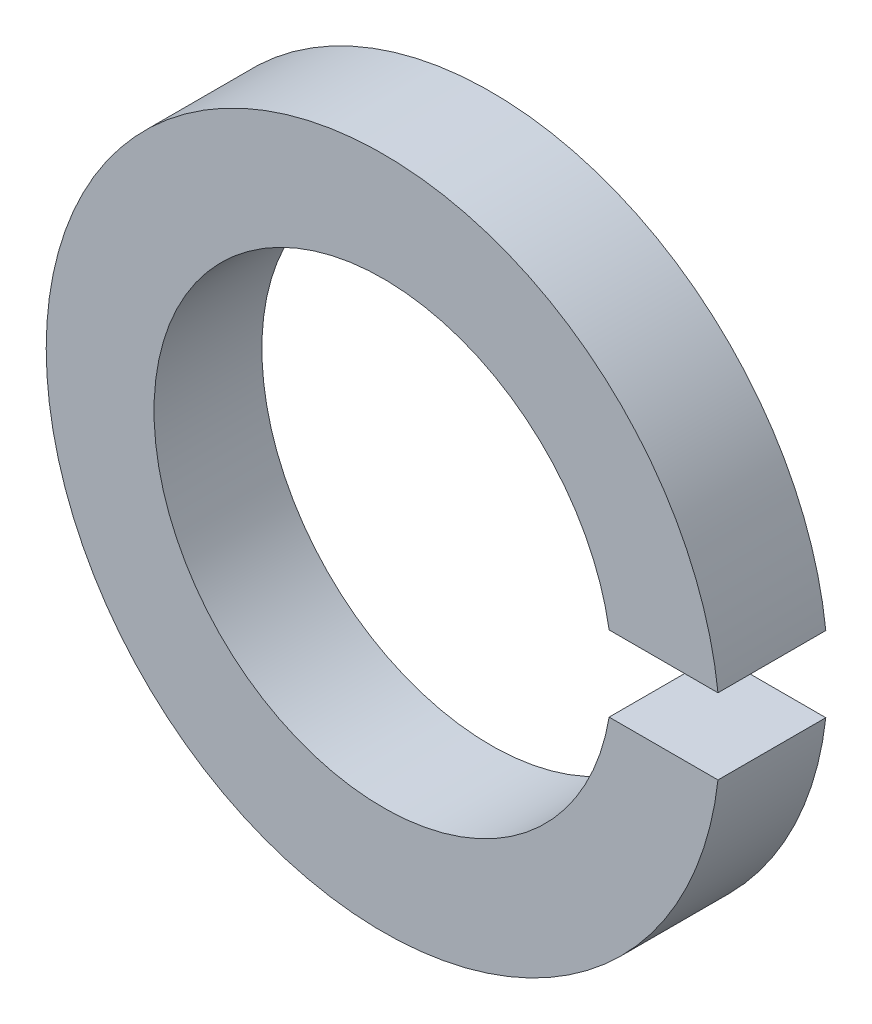
SolidWorks part; units mm, degrees
ref_plane "Спереди" through (0, 0, 0) normal (0, 0, 1) x (1, 0, 0)
ref_plane "Сверху" through (0, 0, 0) normal (0, 1, 0) x (1, 0, 0)
ref_plane "Справа" through (0, 0, 0) normal (1, 0, 0) x (0, 0, -1)
sketch "Эскиз1" plane through (0, 0, 0) normal (0, 0, 1) x (1, 0, 0)
  circle A0 centre (0, 0) radius 3.75
  circle A1 centre (0, 0) radius 2.55
  dimension "D1" = 7.5
  dimension "D2" = 5.1
extrude "Вытянуть1" add sketch "Эскиз1" along normal blind 1.2
sketch "Эскиз2" plane through (0, 0, 1.2) normal (0, 0, 1) x (1, 0, 0)
  line L0 (0, 0) -> (0.123, 0) construction
  line L1 (3.75, 0) -> (-3.75, 0) construction
  line L3 (2.4362, 0.42) -> (3.8364, 0.42)
  line L4 (2.4362, 0.42) -> (2.4362, -0.42)
  line L5 (2.4362, -0.42) -> (3.8364, -0.42)
  line L6 (3.8364, 0.42) -> (3.8364, -0.42)
  circle A0 centre (0, 0) radius 3.75 construction
  dimension "D1" = 0.42
  dimension "D2" = 0.84
extrude "Вырез-Вытянуть1" cut sketch "Эскиз2" against normal through all
